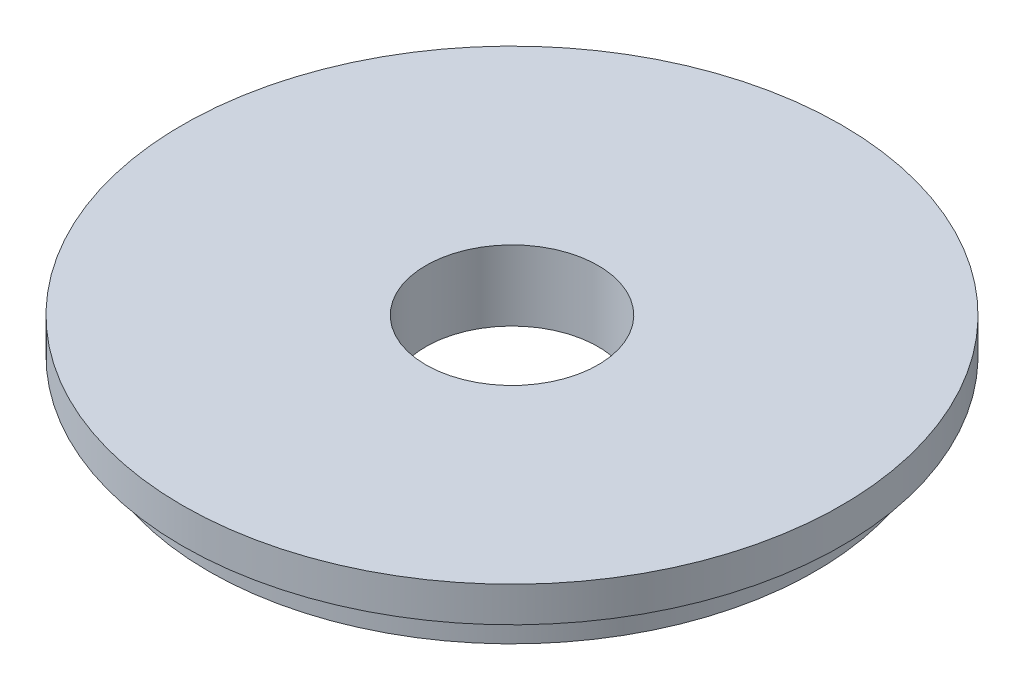
SolidWorks part; units mm, degrees
material "6061-T6 (SS)"
ref_plane "Front Plane" through (0, 0, 0) normal (0, 0, 1) x (1, 0, 0)
ref_plane "Top Plane" through (0, 0, 0) normal (0, 1, 0) x (1, 0, 0)
ref_plane "Right Plane" through (0, 0, 0) normal (1, 0, 0) x (0, 0, -1)
sketch "Sketch1" plane through (0, 0, 0) normal (1, 0, 0) x (0, 0, -1)
  line L0 (0, 6.6219) -> (0, -14.7588) construction
  line L1 (2.4892, -2.032) -> (2.4892, 0)
  line L2 (2.4892, 0) -> (9.525, 0)
  line L3 (9.525, 0) -> (9.525, -1.016)
  line L4 (9.525, -1.016) -> (8.763, -1.016)
  line L5 (8.763, -1.016) -> (8.763, -2.032)
  line L6 (8.763, -2.032) -> (2.4892, -2.032)
  dimension "D1" = 19.05
  dimension "D2" = 1.016
  dimension "D3" = 2.032
  dimension "D4" = 4.9784
  dimension "D5" = 0.762
revolve "Revolve1" add sketch "Sketch1" angle 360 about L0
